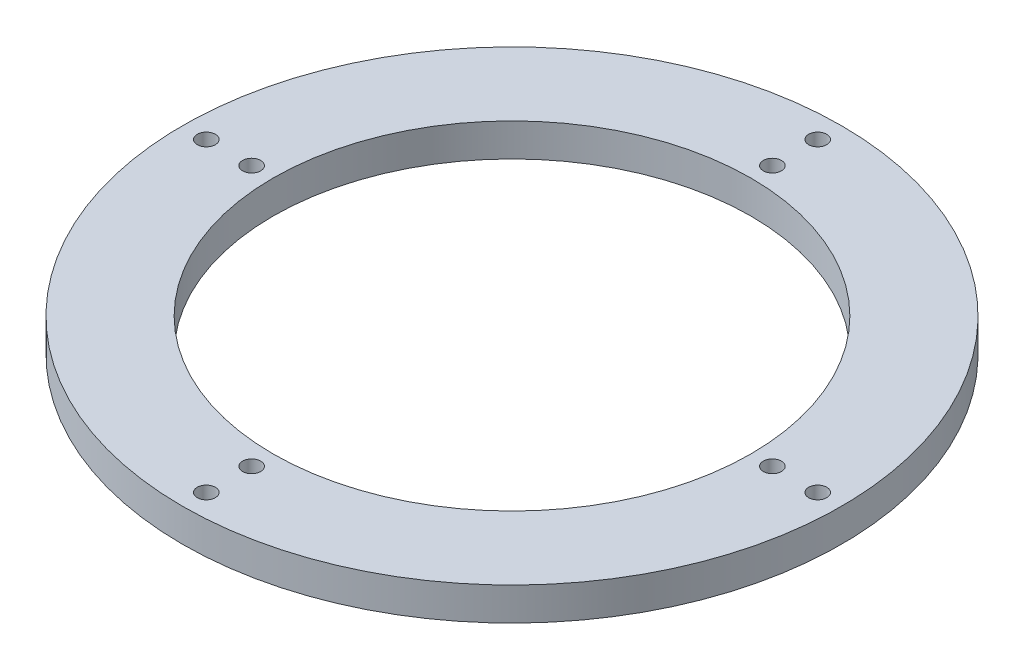
SolidWorks part; units mm, degrees
ref_plane "Front Plane" through (0, 0, 0) normal (0, 0, 1) x (1, 0, 0)
ref_plane "Top Plane" through (0, 0, 0) normal (0, 1, 0) x (1, 0, 0)
ref_plane "Right Plane" through (0, 0, 0) normal (1, 0, 0) x (0, 0, -1)
sketch "Sketch1" plane through (0, 0, 0) normal (0, 1, 0) x (1, 0, 0)
  line L0 (-85.5223, 0) -> (-72.5, 0) construction
  line L1 (-85.5223, 0) -> (-100, 0) construction
  circle A0 centre (0, 0) radius 100
  circle A1 centre (0, 0) radius 72.5
  circle A2 centre (0, 0) radius 85.5223 construction
  circle A4 centre (-79.0112, 0) radius 2.75
  circle A10 centre (-92.7612, 0) radius 2.75
  circle A11 centre (0, 79.0112) radius 2.75
  circle A12 centre (0, 92.7612) radius 2.75
  circle A13 centre (79.0112, 0) radius 2.75
  circle A14 centre (92.7612, 0) radius 2.75
  circle A15 centre (0, -79.0112) radius 2.75
  circle A16 centre (0, -92.7612) radius 2.75
  point P21 (-79.0112, 0)
  point P26 (-92.7612, 0)
  point P29 (0, 0)
  dimension "D1" = 200
  dimension "D2" = 145
  dimension "D3" = 171.0447
  dimension "D4" = 4
  dimension "D10" = 5.5
  dimension "D11" = 5.5
extrude "Boss-Extrude1" add sketch "Sketch1" along normal blind 10
